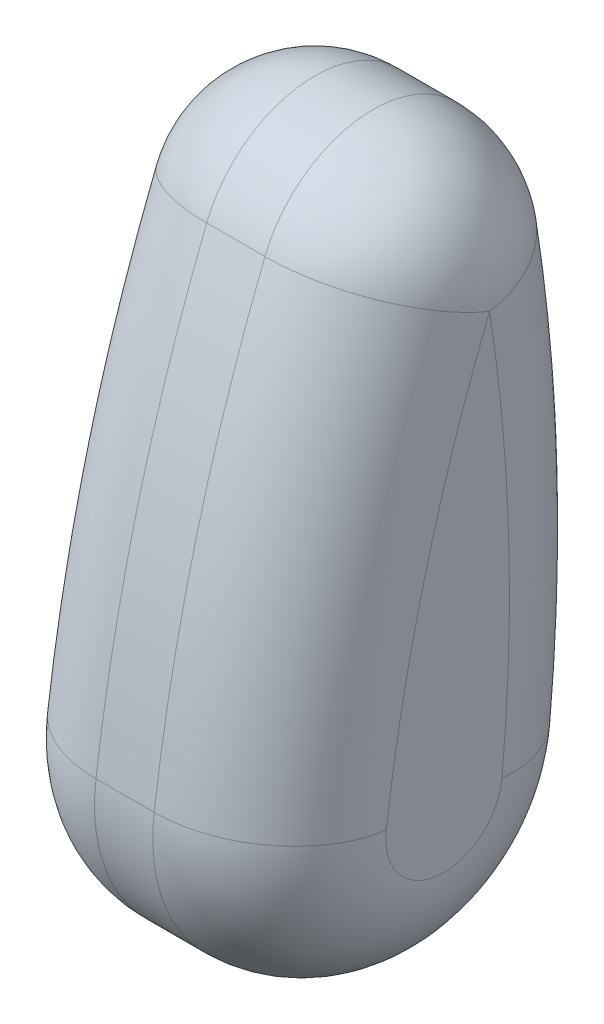
SolidWorks part; units mm, degrees
material "PW90:Mi:0:29:C1:0:1:2:Re:16:"
ref_plane "XY" through (0, 0, 0) normal (0, 0, 1) x (1, 0, 0)
ref_plane "YZ" through (0, 0, 0) normal (0, 1, 0) x (1, 0, 0)
ref_plane "XZ" through (0, 0, 0) normal (1, 0, 0) x (0, 0, -1)
sketch "Sketch8" plane through (0, 0, 0) normal (1, 0, 0) x (0, 0, -1)
  line L0 (5.9396, 192.7601) -> (25.8227, 369.4448) construction
  line L1 (0, 432.2232) -> (0, -432.2232) construction
  arc A0 (-69.6376, 202.4822) -> (81.7874, 185.4418) centre (5.9396, 192.7601) ccw
  arc A1 (76.0022, 377.3605) -> (-21.3425, 388.3151) centre (25.8227, 369.4448) ccw
  arc A2 (-69.6376, 202.4822) -> (-21.3425, 388.3151) centre (686.1348, 105.2605) cw
  arc A3 (76.0022, 377.3605) -> (81.7874, 185.4418) centre (-676.6902, 258.6247) cw
  dimension "D2" = 50.8
  dimension "D4" = 76.2
  dimension "D5" = 762
  dimension "D6" = 762
  dimension "D1" = 6.421
  dimension "D3" = 177.8
extrude "Base-Extrude" add sketch "Sketch8" along normal mid plane 127
fillet "Fillet1" radius 50.8
